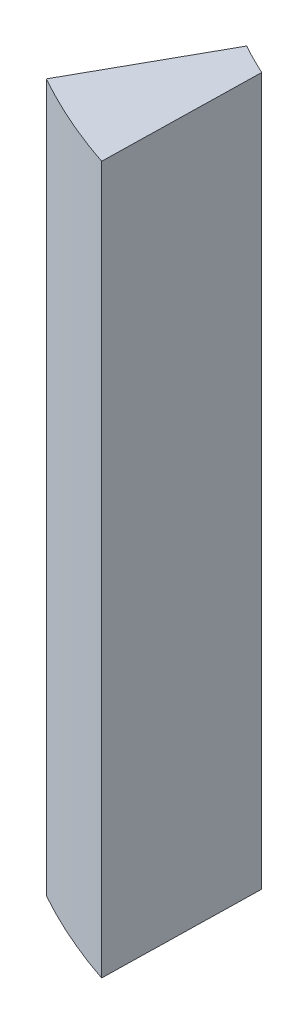
SolidWorks part; units mm, degrees
material "PTFE (general)"
ref_plane "Front Plane" through (0, 0, 0) normal (0, 0, 1) x (1, 0, 0)
ref_plane "Top Plane" through (0, 0, 0) normal (0, 1, 0) x (1, 0, 0)
ref_plane "Right Plane" through (0, 0, 0) normal (1, 0, 0) x (0, 0, -1)
sketch "Sketch1" plane through (0, 0, 0) normal (0, 1, 0) x (1, 0, -0.0097)
  line L0 (-41.3144, -20.7744) -> (-46.2682, -29.4612)
  line L1 (-39.2598, -21.8658) -> (-39.2591, -21.8419)
  line L3 (-39.2598, -21.8658) -> (-39.5768, -32.4913)
  arc A0 (-41.3144, -20.7744) -> (-39.2591, -21.8419) centre (-26.6897, 4.8706) ccw
  arc A1 (-46.2682, -29.4612) -> (-39.5768, -32.4913) centre (-26.6897, 4.8706) ccw
extrude "Boss-Extrude1" add sketch "Sketch1" along normal blind 48
